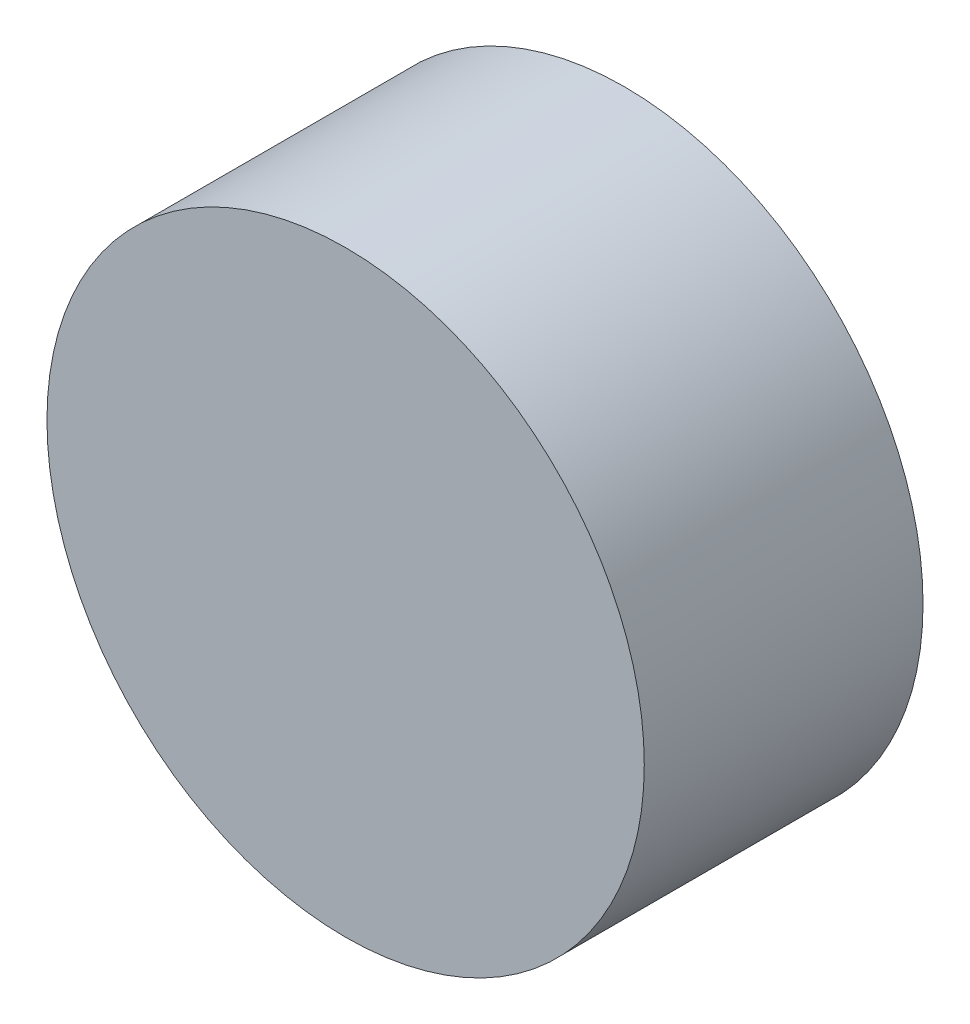
SolidWorks part; units mm, degrees
ref_plane "前视基准面" through (0, 0, 0) normal (0, 0, 1) x (1, 0, 0)
ref_plane "上视基准面" through (0, 0, 0) normal (0, 1, 0) x (1, 0, 0)
ref_plane "右视基准面" through (0, 0, 0) normal (1, 0, 0) x (0, 0, -1)
sketch "草图1" plane through (0, 0, 0) normal (0, 0, 1) x (1, 0, 0)
  circle A0 centre (0, 0) radius 60
  dimension "D1" = 120
extrude "凸台-拉伸1" add sketch "草图1" along normal mid plane 56
